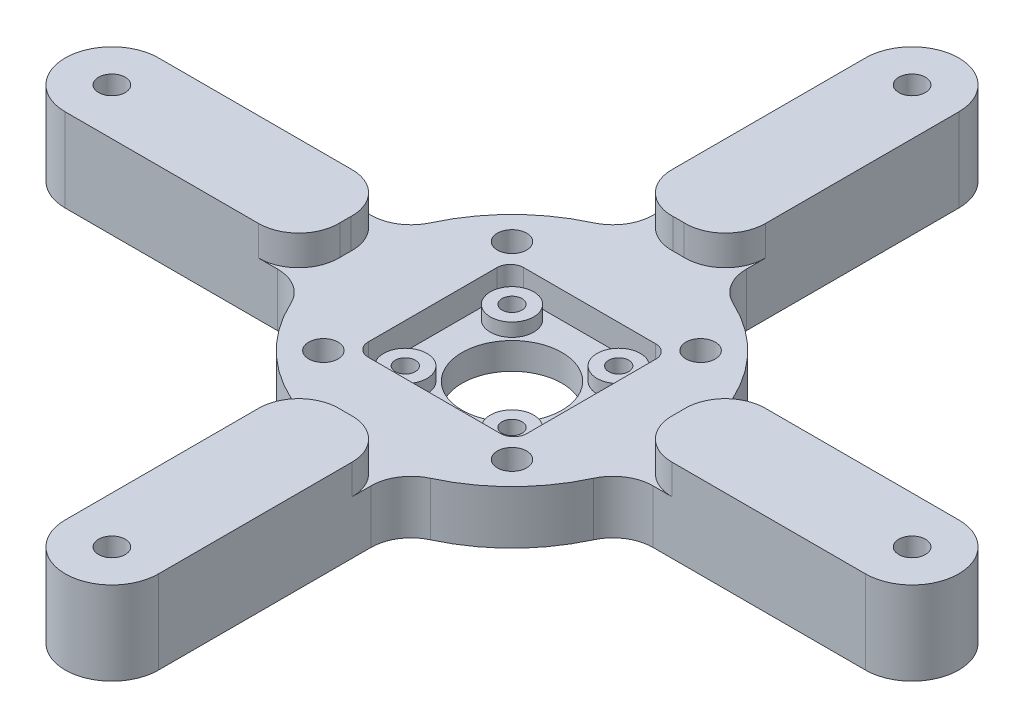
SolidWorks part; units mm, degrees
ref_plane "Plan de face" through (0, 0, 0) normal (0, 0, 1) x (1, 0, 0)
ref_plane "Plan de dessus" through (0, 0, 0) normal (0, 1, 0) x (1, 0, 0)
ref_plane "Plan de droite" through (0, 0, 0) normal (1, 0, 0) x (0, 0, -1)
sketch "Esquisse1" plane through (0, 0, 0) normal (0, 1, 0) x (1, 0, 0)
  line L0 (0, 20) -> (0, 0) construction
  line L1 (0, 0) -> (14.1421, 14.1421) construction
  line L2 (-30, 0) -> (30, 0) construction
  line L3 (8, 8) -> (-8, 8) construction
  line L4 (8, 8) -> (8, -8) construction
  line L5 (8, -8) -> (-8, -8) construction
  line L6 (-8, 8) -> (-8, -8) construction
  line L7 (8, 8) -> (-8, -8) construction
  line L8 (8, -8) -> (-8, 8) construction
  line L9 (60, 7) -> (24, 7)
  line L10 (60, -7) -> (24, -7)
  line L11 (7, -60) -> (7, -24)
  line L12 (-7, -60) -> (-7, -24)
  line L13 (-60, -7) -> (-24, -7)
  line L14 (-60, 7) -> (-24, 7)
  line L15 (-7, 60) -> (-7, 24)
  line L16 (7, 60) -> (7, 24)
  circle A0 centre (0, 0) radius 20 construction
  circle A1 centre (14.1421, 14.1421) radius 2.2
  circle A2 centre (14.1421, -14.1421) radius 2.2
  circle A3 centre (-14.1421, -14.1421) radius 2.2
  circle A4 centre (-14.1421, 14.1421) radius 2.2
  circle A5 centre (-8, 8) radius 1.5
  circle A6 centre (-8, -8) radius 1.5
  circle A7 centre (8, -8) radius 1.5
  circle A8 centre (8, 8) radius 1.5
  circle A9 centre (0, 0) radius 60 construction
  circle A10 centre (60, 0) radius 2
  circle A11 centre (0, -60) radius 2
  circle A12 centre (-60, 0) radius 2
  circle A13 centre (0, 60) radius 2
  arc A14 (24, 7) -> (7, 24) centre (0, 0) ccw
  arc A15 (60, -7) -> (60, 7) centre (60, 0) ccw
  arc A16 (-7, -60) -> (7, -60) centre (0, -60) ccw
  arc A17 (-60, 7) -> (-60, -7) centre (-60, 0) ccw
  arc A18 (7, 60) -> (-7, 60) centre (0, 60) ccw
  arc A19 (7, -24) -> (24, -7) centre (0, 0) ccw
  arc A20 (-24, -7) -> (-7, -24) centre (0, 0) ccw
  arc A21 (-7, 24) -> (-24, 7) centre (0, 0) ccw
  point P15 (0, 0)
  point P25 (-30, 0)
  point P36 (0, 0)
  point P57 (0, 0)
  dimension "D1" = 40
  dimension "D2" = 45
  dimension "D4" = 4.4
  dimension "D5" = 3
  dimension "D8" = 120
  dimension "D9" = 4
  dimension "D11" = 50
  dimension "D6" = 16
  dimension "D7" = 16
  dimension "D12" = 14
  dimension "D3" = 4
  dimension "D10" = 4
  dimension "D13" = 4
extrude "Boss.-Extru.1" add sketch "Esquisse1" along normal blind 8
sketch "Esquisse2" plane through (0, 8, 0) normal (0, 1, 0) x (1, 0, 0)
  line L1 (11.9, 11.65) -> (-11.9, 11.65)
  line L2 (11.9, 11.65) -> (11.9, -11.65)
  line L3 (11.9, -11.65) -> (-11.9, -11.65)
  line L4 (-11.9, 11.65) -> (-11.9, -11.65)
  line L5 (11.9, 11.65) -> (-11.9, -11.65) construction
  line L6 (11.9, -11.65) -> (-11.9, 11.65) construction
  point P0 (0, 0)
  point P6 (0, 0)
  point P7 (0, 0)
  dimension "D1" = 23.3
  dimension "D2" = 23.8
extrude "Enlèv. mat.-Extru.1" cut sketch "Esquisse2" against normal blind 2
fillet "Congé1" radius 2 4 edges at (-11.9, 7, 11.65) (11.9, 7, 11.65) (11.9, 7, -11.65) (-11.9, 7, -11.65)
sketch "Esquisse4" plane through (0, 6, 0) normal (0, 1, 0) x (1, 0, 0)
  line L4 (-11.9, 9.65) -> (-11.9, -9.65)
  line L5 (-9.9, -11.65) -> (9.9, -11.65)
  line L6 (11.9, -9.65) -> (11.9, 9.65)
  line L7 (9.9, 11.65) -> (-9.9, 11.65)
  line L8 (-11.9, 9.65) -> (-11.9, -9.65)
  line L9 (-9.9, -11.65) -> (9.9, -11.65)
  line L10 (11.9, -9.65) -> (11.9, 9.65)
  line L11 (9.9, 11.65) -> (-9.9, 11.65)
  circle A0 centre (8, 8) radius 3.25
  circle A1 centre (-8, 8) radius 3.25
  circle A2 centre (-8, -8) radius 3.25
  circle A3 centre (8, -8) radius 3.25
  arc A4 (-11.9, -9.65) -> (-9.9, -11.65) centre (-9.9, -9.65) ccw
  arc A5 (9.9, -11.65) -> (11.9, -9.65) centre (9.9, -9.65) ccw
  arc A6 (11.9, 9.65) -> (9.9, 11.65) centre (9.9, 9.65) ccw
  arc A7 (-9.9, 11.65) -> (-11.9, 9.65) centre (-9.9, 9.65) ccw
  arc A8 (-11.9, -9.65) -> (-9.9, -11.65) centre (-9.9, -9.65) ccw
  arc A9 (9.9, -11.65) -> (11.9, -9.65) centre (9.9, -9.65) ccw
  arc A10 (11.9, 9.65) -> (9.9, 11.65) centre (9.9, 9.65) ccw
  arc A11 (-9.9, 11.65) -> (-11.9, 9.65) centre (-9.9, 9.65) ccw
  dimension "D2" = 6.5
  dimension "D1" = 0
extrude "Enlèv. mat.-Extru.2" cut sketch "Esquisse4" against normal blind 2
sketch "Esquisse5" plane through (0, 4, 0) normal (0, 1, 0) x (1, 0, 0)
  circle A0 centre (0, 0) radius 7.5
  dimension "D1" = 15
extrude "Enlèv. mat.-Extru.3" cut sketch "Esquisse5" against normal through all
sketch "Esquisse6" plane through (0, 8, 0) normal (0, 1, 0) x (1, 0, 0)
  line L8 (24, -7) -> (60, -7)
  line L9 (60, 7) -> (24, 7)
  line L10 (7, 24) -> (7, 60)
  line L11 (-7, 60) -> (-7, 24)
  line L12 (-24, 7) -> (-60, 7)
  line L13 (-60, -7) -> (-24, -7)
  line L14 (-7, -24) -> (-7, -60)
  line L15 (7, -60) -> (7, -24)
  line L16 (24, -7) -> (60, -7)
  line L17 (60, 7) -> (24, 7)
  line L18 (7, 24) -> (7, 60)
  line L19 (-7, 60) -> (-7, 24)
  line L20 (-24, 7) -> (-60, 7)
  line L21 (-60, -7) -> (-24, -7)
  line L22 (-7, -24) -> (-7, -60)
  line L23 (7, -60) -> (7, -24)
  circle A0 centre (-60, 0) radius 2 construction
  circle A1 centre (-60, 0) radius 2
  circle A2 centre (0, 60) radius 2 construction
  circle A3 centre (0, 60) radius 2
  circle A4 centre (60, 0) radius 2 construction
  circle A5 centre (60, 0) radius 2
  circle A6 centre (0, -60) radius 2 construction
  circle A7 centre (0, -60) radius 2
  arc A8 (-24, 7) -> (-24, -7) centre (0, 0) ccw
  arc A9 (7, 24) -> (-7, 24) centre (0, 0) ccw
  arc A10 (7, -24) -> (24, -7) centre (0, 0) ccw
  arc A11 (60, -7) -> (60, 7) centre (60, 0) ccw
  arc A12 (24, 7) -> (7, 24) centre (0, 0) ccw
  arc A13 (7, 60) -> (-7, 60) centre (0, 60) ccw
  arc A14 (-7, 24) -> (-24, 7) centre (0, 0) ccw
  arc A15 (-60, 7) -> (-60, -7) centre (-60, 0) ccw
  arc A16 (-24, -7) -> (-7, -24) centre (0, 0) ccw
  arc A17 (-7, -60) -> (7, -60) centre (0, -60) ccw
  arc A18 (-7, -24) -> (7, -24) centre (0, 0) ccw
  arc A19 (60, -7) -> (60, 7) centre (60, 0) ccw
  arc A20 (24, -7) -> (24, 7) centre (0, 0) ccw
  arc A21 (7, 60) -> (-7, 60) centre (0, 60) ccw
  arc A23 (-60, 7) -> (-60, -7) centre (-60, 0) ccw
  arc A25 (-7, -60) -> (7, -60) centre (0, -60) ccw
  dimension "D1" = 0
extrude "Boss.-Extru.2" add sketch "Esquisse6" along normal blind 4.5
fillet "Congé2" radius 6 8 edges at (7, 10.25, 24) (-7, 10.25, 24) (24, 10.25, -7) (24, 10.25, 7) (-7, 10.25, -24) (7, 10.25, -24) (-24, 10.25, -7) (-24, 10.25, 7)
fillet "Congé3" radius 6 8 edges at (-7, 4, -24) (-24, 4, -7) (24, 4, -7) (7, 4, -24) (24, 4, 7) (7, 4, 24) (-7, 4, 24) (-24, 4, 7)
